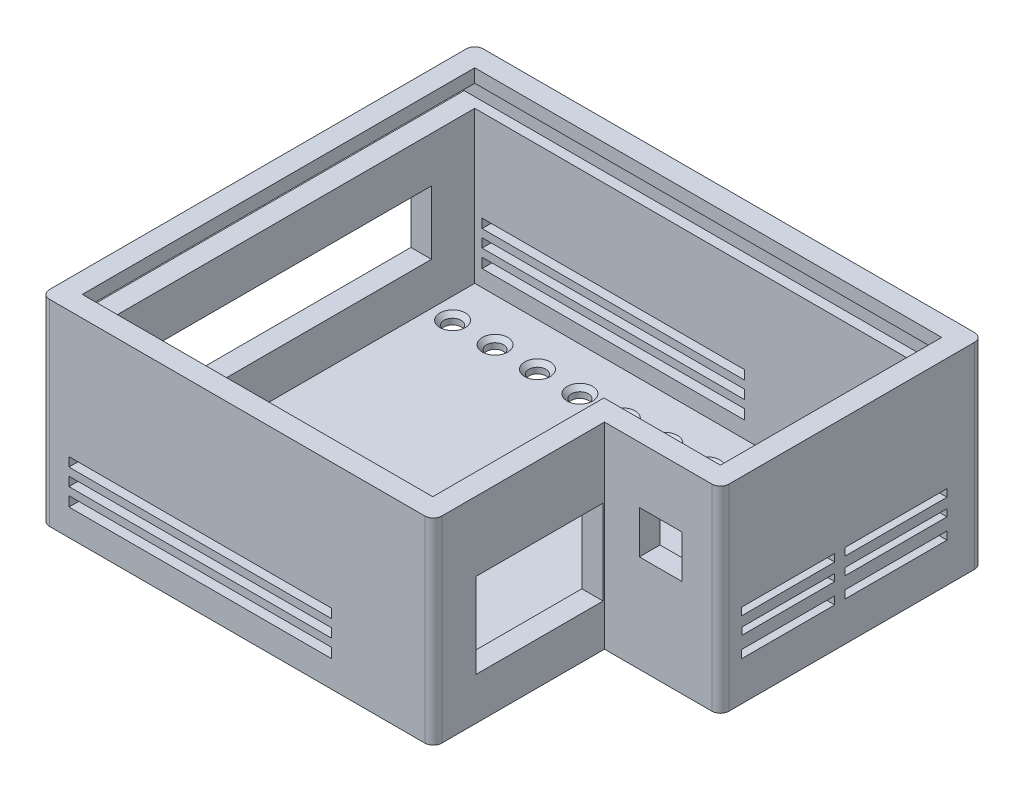
SolidWorks part; units mm, degrees
ref_plane "Front Plane" through (0, 0, 0) normal (0, 0, 1) x (1, 0, 0)
ref_plane "Top Plane" through (0, 0, 0) normal (0, 1, 0) x (1, 0, 0)
ref_plane "Right Plane" through (0, 0, 0) normal (1, 0, 0) x (0, 0, -1)
sketch "Sketch1" plane through (0, 0, 0) normal (0, 1, 0) x (1, 0, 0)
  line L0 (104.775, 0) -> (139.775, 0)
  line L1 (0, 0) -> (104.775, 0)
  line L2 (0, 0) -> (0, -117.475)
  line L3 (0, -117.475) -> (104.902, -117.475)
  line L4 (104.902, -66.2424) -> (104.902, -117.475)
  line L5 (139.775, 0) -> (139.775, -66.2424)
  line L6 (-3, -120.475) -> (104.902, -120.475)
  line L7 (104.902, -117.475) -> (104.902, -66.2424)
  line L8 (104.902, -66.2424) -> (139.775, -66.2424)
  line L9 (-3, 3) -> (-3, -120.475)
  line L10 (-3, 3) -> (104.775, 3)
  line L11 (104.775, 3) -> (142.775, 3)
  line L12 (142.775, 3) -> (142.775, -69.2424)
  line L13 (108.077, -69.2424) -> (142.775, -69.2424)
  line L14 (104.902, -66.2424) -> (107.9494, -66.2424)
  line L16 (108.077, -120.475) -> (104.902, -120.475)
  line L17 (-6.175, 6.175) -> (-6.175, -123.65)
  line L18 (104.902, -69.2424) -> (142.775, -69.2424) construction
  line L19 (-6.175, -123.65) -> (104.902, -123.65)
  line L20 (111.252, -123.65) -> (104.902, -123.65)
  line L21 (111.252, -72.4174) -> (111.252, -123.65)
  line L22 (111.252, -72.4174) -> (145.95, -72.4174)
  line L23 (145.95, 6.175) -> (145.95, -72.4174)
  line L24 (104.775, 6.175) -> (145.95, 6.175)
  line L25 (-6.175, 6.175) -> (104.775, 6.175)
  line L26 (108.077, -69.2424) -> (108.077, -120.475) construction
  dimension "D1" = 104.775
  dimension "D2" = 117.475
  dimension "D3" = 35
  dimension "D5" = 104.902
  dimension "D6" = 51.2326
  dimension "D8" = 51.2326
  dimension "D4" = 3
  dimension "D7" = 3.175
extrude "Boss-Extrude1" add sketch "Sketch1" along normal blind 55.88
ref_plane "Plane1" through (0, 0, 0) normal (0, 0, 1) x (1, 0, 0)
sketch "Sketch23" plane through (0, 0, 72.4174) normal (0, 0, 1) x (1, 0, 0)
  line L9 (121.6901, 38.9689) -> (134.3901, 38.9689)
  line L10 (121.6901, 38.9689) -> (121.6901, 26.1561)
  line L11 (121.6901, 26.1561) -> (134.3901, 26.1561)
  line L12 (134.3901, 38.9689) -> (134.3901, 26.1561)
  dimension "D1" = 12.8128
  dimension "D2" = 12.7
sketch "Sketch25" plane through (-6.175, 0, 0) normal (-1, 0, 0) x (0, 0, 1)
  line L1 (-6.175, 55.88) -> (-6.175, 0) construction
  line L4 (12.9455, 12.7) -> (101.8455, 12.7)
  line L5 (12.9455, 12.7) -> (12.9455, 31.75)
  line L6 (12.9455, 31.75) -> (101.8455, 31.75)
  line L7 (101.8455, 12.7) -> (101.8455, 31.75)
  dimension "D1" = 88.9
  dimension "D2" = 19.05
  dimension "D3" = 19.1205
extrude "Cut-Extrude9" cut sketch "Sketch25" against normal blind 45
sketch "Sketch26" plane through (145.95, 0, 0) normal (1, 0, 0) x (0, 0, -1)
  line L0 (-35.1213, 22.0738) -> (-4.5981, 22.0738)
  line L1 (-66.1038, 11.0882) -> (-38.1973, 11.0882)
  line L2 (-66.1038, 11.0882) -> (-66.1038, 8.7152)
  line L3 (-66.1038, 8.7152) -> (-38.1973, 8.7152)
  line L4 (-4.5981, 11.0882) -> (-4.5981, 8.7152)
  line L5 (-65.9512, 14.7529) -> (-38.1973, 14.7529)
  line L6 (-65.9512, 14.7529) -> (-65.9512, 16.8722)
  line L7 (-65.9512, 16.8722) -> (-38.1973, 16.8722)
  line L8 (-4.5981, 14.7529) -> (-4.5981, 16.8722)
  line L9 (-66.0841, 19.8363) -> (-38.1973, 19.8363)
  line L10 (-66.0841, 19.8363) -> (-66.0841, 22.0738)
  line L11 (-66.0841, 22.0738) -> (-38.1973, 22.0738)
  line L12 (-4.5981, 19.8363) -> (-4.5981, 22.0738)
  line L14 (-38.1973, 22.0738) -> (-38.1973, 19.8363)
  line L16 (-35.1213, 22.0738) -> (-35.1213, 19.8363)
  line L17 (-35.1213, 19.8363) -> (-4.5981, 19.8363)
  line L18 (-35.1213, 16.8722) -> (-35.1213, 14.7529)
  line L19 (-38.1973, 16.8722) -> (-38.1973, 14.7529)
  line L20 (-35.1213, 8.7152) -> (-4.5981, 8.7152)
  line L21 (-35.1213, 11.0882) -> (-4.5981, 11.0882)
  line L22 (-35.1213, 11.0882) -> (-35.1213, 8.7152)
  line L23 (-38.1973, 11.0882) -> (-38.1973, 8.7152)
  line L24 (-35.1213, 14.7529) -> (-4.5981, 14.7529)
  line L25 (-35.1213, 16.8722) -> (-4.5981, 16.8722)
extrude "Cut-Extrude10" cut sketch "Sketch26" against normal blind 45
sketch "Sketch27" plane through (0, 0, -6.175) normal (0, 0, -1) x (-1, 0, 0)
  line L1 (-2.1913, 4.9397) -> (-80.721, 4.9397)
  line L2 (-2.1913, 4.9397) -> (-2.1913, 7.8744)
  line L3 (-2.1913, 7.8744) -> (-80.721, 7.8744)
  line L4 (-80.721, 4.9397) -> (-80.721, 7.8744)
  line L5 (-80.721, 10.2406) -> (-2.1913, 10.2406)
  line L6 (-80.721, 10.2406) -> (-80.721, 12.9398)
  line L7 (-80.721, 12.9398) -> (-2.1913, 12.9398)
  line L8 (-2.1913, 10.2406) -> (-2.1913, 12.9398)
  line L9 (-2.1913, 15.306) -> (-80.721, 15.306)
  line L10 (-2.1913, 15.306) -> (-2.1913, 18.0154)
  line L11 (-2.1913, 18.0154) -> (-80.721, 18.0154)
  line L12 (-80.721, 15.306) -> (-80.721, 18.0154)
extrude "Cut-Extrude11" cut sketch "Sketch27" against normal blind 254
extrude "Cut-Extrude12" cut sketch "Sketch23" against normal blind 50.8
sketch "Sketch31" plane through (-6.175, 0, 0) normal (-1, 0, 0) x (0, 0, 1)
  line L3 (-3, 45.3704) -> (-3, 51.8754)
  line L4 (-3, 51.8754) -> (120.5647, 51.8754)
  line L7 (120.5647, 51.8754) -> (120.5647, 45.3704)
  line L8 (120.5647, 45.3704) -> (-3, 45.3704)
extrude "Cut-Extrude13" cut sketch "Sketch31" against normal blind 113.8
sketch "Sketch34" plane through (107.625, 0, 0) normal (-1, 0, 0) x (0, 0, 1)
  line L1 (66.2424, 45.3704) -> (69.0364, 45.3704)
  line L2 (66.2424, 45.3704) -> (66.2424, 51.3704)
  line L3 (66.2424, 51.3704) -> (69.0364, 51.3704)
  line L4 (69.0364, 45.3704) -> (69.0364, 51.3704)
  line L5 (-3, 45.3704) -> (0, 45.3704)
  line L6 (-3, 45.3704) -> (-3, 51.8754)
  line L7 (-3, 51.8754) -> (0, 51.8754)
  line L8 (0, 45.3704) -> (0, 51.8754)
  dimension "D1" = 6
  dimension "D2" = 2.794
extrude "Cut-Extrude14" cut sketch "Sketch34" against normal blind 35.8
sketch "Sketch35" plane through (139.775, 0, 0) normal (-1, 0, 0) x (0, 0, 1)
  line L1 (0, 45.3704) -> (66.2424, 45.3704)
  line L2 (0, 45.3704) -> (0, 51.3704)
  line L3 (0, 51.3704) -> (66.2424, 51.3704)
  line L4 (66.2424, 45.3704) -> (66.2424, 51.3704)
extrude "Cut-Extrude15" cut sketch "Sketch35" against normal blind 2.8
sketch "Sketch36" plane through (0, 0, 0) normal (0, -1, 0) x (1, 0, 0)
  line L0 (111.252, 72.4174) -> (111.252, 123.65)
  line L1 (111.252, 123.65) -> (-6.175, 123.65)
  line L2 (-6.175, 123.65) -> (-6.175, -6.175)
  line L3 (-6.175, -6.175) -> (145.95, -6.175)
  line L4 (145.95, -6.175) -> (145.95, 72.4174)
  line L5 (145.95, 72.4174) -> (111.252, 72.4174)
extrude "Boss-Extrude2" add sketch "Sketch36" along normal blind 3
ref_plane "Plane2" through (145.95, -3, 72.4174) normal (0, -1, 0) x (-1, 0, 0)
sketch "Sketch37" plane through (145.95, -3, 72.4174) normal (0, -1, 0) x (1, 0, 0)
  line L0 (0, -78.5924) -> (0, 0) construction
  line L1 (-152.125, -78.5924) -> (0, -78.5924) construction
  circle A22 centre (-12.7, -59.5424) radius 2.54
  circle A26 centre (-63.5, 29.3576) radius 2.54
  circle A27 centre (-114.3, 29.3576) radius 2.54
  circle A28 centre (-25.4, -59.5424) radius 2.54
  circle A29 centre (-38.1, -59.5424) radius 2.54
  circle A30 centre (-50.8, -59.5424) radius 2.54
  circle A31 centre (-63.5, -59.5424) radius 2.54
  circle A32 centre (-76.2, -59.5424) radius 2.54
  circle A33 centre (-88.9, -59.5424) radius 2.54
  circle A34 centre (-101.6, -59.5424) radius 2.54
  circle A35 centre (-114.3, -59.5424) radius 2.54
  circle A36 centre (-127, -59.5424) radius 2.54
  circle A37 centre (-139.7, -59.5424) radius 2.54
  point P4 (0, 0)
  dimension "D1" = 5.08
  dimension "D2" = 12.7
  dimension "D3" = 19.05
  dimension "D5" = 88.9
  dimension "D7" = 5.08
  dimension "D8" = 5.08
  dimension "D9" = 11
  dimension "D12" = 88.9
  dimension "D15" = 50.8
sketch "Sketch38" plane through (111.252, 0, 0) normal (1, 0, 0) x (0, 0, -1)
  line L0 (-72.4174, -3) -> (-123.65, -3) construction
  line L1 (-110.95, 35.1) -> (-72.85, 35.1)
  line L2 (-110.95, 35.1) -> (-110.95, 9.7)
  line L3 (-110.95, 9.7) -> (-72.85, 9.7)
  line L4 (-72.85, 35.1) -> (-72.85, 9.7)
  line L5 (-123.65, 55.88) -> (-123.65, -3) construction
  dimension "D1" = 12.7
  dimension "D2" = 12.7
  dimension "D3" = 50.8
  dimension "D4" = 38.1
extrude "Cut-Extrude17" cut sketch "Sketch38" against normal blind 10.16
fillet "Fillet1" radius 2.54 5 edges at (-6.175, 26.44, 123.65) (-6.175, 26.44, -6.175) (111.252, 26.44, 123.65) (145.95, 26.44, 72.4174) (145.95, 26.44, -6.175)
extrude "Cut-Extrude18" cut sketch "Sketch37" against normal blind 5.842
chamfer "Chamfer1" distance 1.27 angle 45 13 edges at (31.65, 0, 104.315) (82.45, 0, 104.315) (6.25, 0, 15.415) (18.95, 0, 15.415) (31.65, 0, 15.415) (44.35, 0, 15.415) (57.05, 0, 15.415) (69.75, 0, 15.415) (82.45, 0, 15.415) (95.15, 0, 15.415) (107.85, 0, 15.415) (120.55, 0, 15.415) (133.25, 0, 15.415)
